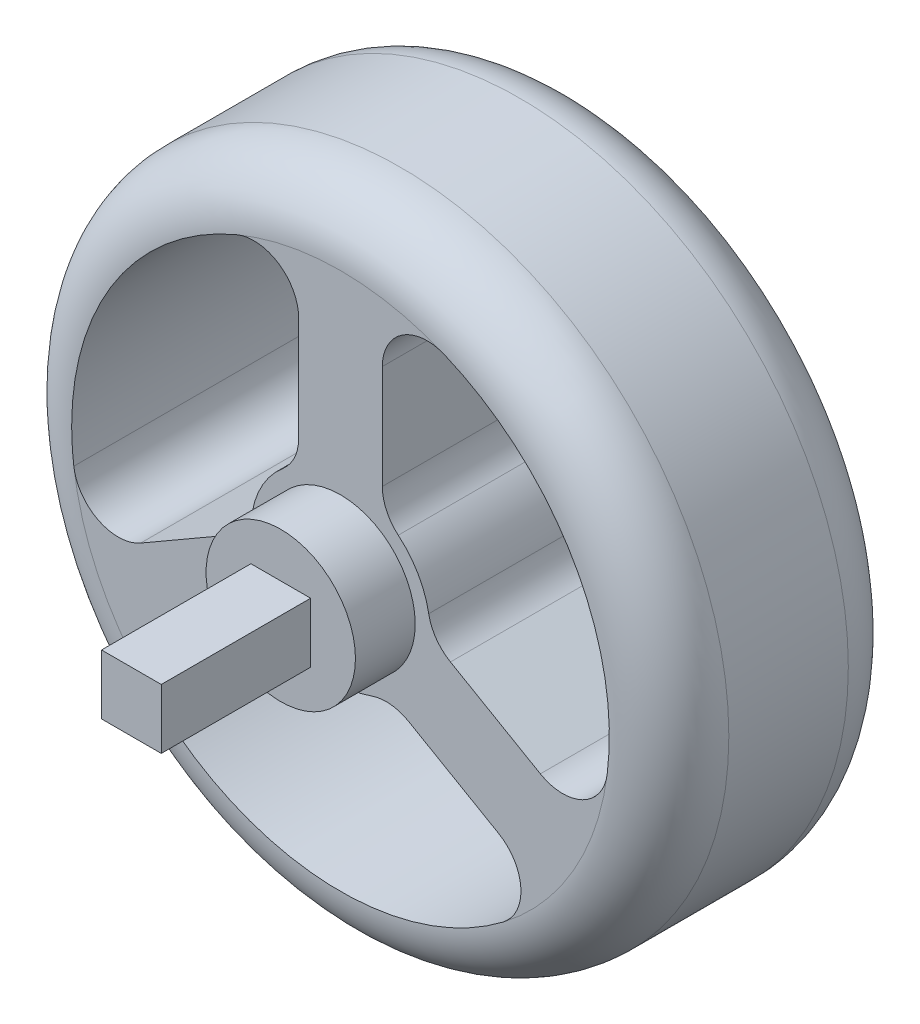
SolidWorks part; units mm, degrees
material "Rubber"
ref_plane "Front Plane" through (0, 0, 0) normal (0, 0, 1) x (1, 0, 0)
ref_plane "Top Plane" through (0, 0, 0) normal (0, 1, 0) x (1, 0, 0)
ref_plane "Right Plane" through (0, 0, 0) normal (1, 0, 0) x (0, 0, -1)
sketch "Sketch1" plane through (0, 0, 0) normal (0, 0, 1) x (1, 0, 0)
  circle A0 centre (0, 0) radius 27.94
  dimension "D1" = 55.88
extrude "Boss-Extrude1" add sketch "Sketch1" along normal blind 20.32
sketch "Sketch2" plane through (0, 0, 0) normal (0, 0, -1) x (-1, 0, 0)
  circle A0 centre (0, 0) radius 6.35
  dimension "D2" = 12.7
extrude "Boss-Extrude2" add sketch "Sketch2" along normal blind 20.32
sketch "Sketch3" plane through (0, 0, -20.32) normal (0, 0, -1) x (-1, 0, 0)
  circle A0 centre (0, 0) radius 27.94
  dimension "D2" = 55.88
extrude "Boss-Extrude3" add sketch "Sketch3" along normal blind 20.32
fillet "Fillet1" radius 5.08 1 edges at (27.94, 0, 20.32)
fillet "Fillet2" radius 5.08 1 edges at (27.94, 0, 0)
fillet "Fillet3" radius 5.08 1 edges at (-27.94, 0, -20.32)
fillet "Fillet4" radius 5.08 1 edges at (-27.94, 0, -40.64)
sketch "Sketch4" plane through (0, 0, -40.64) normal (0, 0, -1) x (-1, 0, 0)
  line L0 (0, 7.62) -> (0, 22.86) construction
  line L1 (-3.556, 8.74) -> (-3.556, 17.5683)
  line L2 (3.556, 8.74) -> (3.556, 17.5683)
  line L3 (9.347, -1.2904) -> (16.9926, -5.7046)
  line L4 (5.791, -7.4496) -> (13.4366, -11.8637)
  line L5 (-5.791, -7.4496) -> (-13.4366, -11.8637)
  line L6 (-9.347, -1.2904) -> (-16.9926, -5.7046)
  arc A0 (-13.8379, -18.1959) -> (13.8379, -18.1959) centre (0, 0) ccw
  arc A1 (7.5014, 1.3394) -> (4.9107, 5.8266) centre (0, 0) ccw
  arc A2 (-4.9107, 5.8266) -> (-7.5014, 1.3394) centre (0, 0) ccw
  arc A3 (-2.5907, -7.1661) -> (2.5907, -7.1661) centre (0, 0) ccw
  arc A4 (-3.556, 17.5683) -> (-8.8392, 21.0819) centre (-7.366, 17.5683) ccw
  arc A5 (8.8392, 21.0819) -> (3.556, 17.5683) centre (7.366, 17.5683) ccw
  arc A6 (-4.9107, 5.8266) -> (-3.556, 8.74) centre (-7.366, 8.74) ccw
  arc A7 (3.556, 8.74) -> (4.9107, 5.8266) centre (7.366, 8.74) ccw
  arc A8 (16.9926, -5.7046) -> (22.6771, -2.886) centre (18.8976, -2.405) ccw
  arc A9 (7.5014, 1.3394) -> (9.347, -1.2904) centre (11.252, 2.0092) ccw
  arc A10 (5.791, -7.4496) -> (2.5907, -7.1661) centre (3.886, -10.7491) ccw
  arc A11 (13.8379, -18.1959) -> (13.4366, -11.8637) centre (11.5316, -15.1633) ccw
  arc A12 (-13.4366, -11.8637) -> (-13.8379, -18.1959) centre (-11.5316, -15.1633) ccw
  arc A13 (-2.5907, -7.1661) -> (-5.791, -7.4496) centre (-3.886, -10.7491) ccw
  arc A14 (-9.347, -1.2904) -> (-7.5014, 1.3394) centre (-11.252, 2.0092) ccw
  arc A15 (-22.6771, -2.886) -> (-16.9926, -5.7046) centre (-18.8976, -2.405) ccw
  arc A16 (22.6771, -2.886) -> (8.8392, 21.0819) centre (0, 0) ccw
  arc A17 (-8.8392, 21.0819) -> (-22.6771, -2.886) centre (0, 0) ccw
  point P46 (0, 0)
  dimension "D2" = 45.72
  dimension "D3" = 15.24
  dimension "D6" = 7.62
  dimension "D7" = 7.62
  dimension "D8" = 7.62
  dimension "D9" = 7.62
  dimension "D4" = 3.556
  dimension "D5" = 3.556
  dimension "D10" = 3
sketch "Sketch5" plane through (0, 0, 0) normal (0, 1, 0) x (1, 0, 0)
  line L0 (0, 32.8922) -> (0, -10.16) construction
extrude "Cut-Extrude1" cut sketch "Sketch4" against normal through all
ref_plane "Plane1" through (0, 0, 0) normal (0, 0, -1) x (-1, 0, 0)
sketch "Sketch6" plane through (0, 0, 0) normal (0, 0, -1) x (-1, 0, 0)
  circle A0 centre (0, 0) radius 27.94
extrude "Cut-Extrude2" cut sketch "Sketch6" against normal through all
sketch "Sketch7" plane through (0, 0, 0) normal (0, 0, 1) x (1, 0, 0)
  circle A1 centre (0, 0) radius 6.35
  circle A2 centre (0, 0) radius 6.35
  dimension "D1" = 0
extrude "Cut-Extrude3" cut sketch "Sketch7" against normal blind 5.08
sketch "Sketch8" plane through (0, 0, -5.08) normal (0, 0, 1) x (1, 0, 0)
  line L1 (-2.54, 2.54) -> (2.54, 2.54)
  line L2 (-2.54, 2.54) -> (-2.54, -2.54)
  line L3 (-2.54, -2.54) -> (2.54, -2.54)
  line L4 (2.54, 2.54) -> (2.54, -2.54)
  line L5 (-2.54, 2.54) -> (2.54, -2.54) construction
  line L6 (-2.54, -2.54) -> (2.54, 2.54) construction
  circle A1 centre (0, 0) radius 6.35
  circle A2 centre (0, 0) radius 6.35 construction
  dimension "D2" = 5.08
  dimension "D3" = 5.08
  dimension "D1" = 0
sketch "Sketch9" plane through (0, 0, -5.08) normal (0, 0, 1) x (1, 0, 0)
  circle A1 centre (0, 0) radius 6.35
  circle A2 centre (0, 0) radius 6.35
  dimension "D1" = 0
extrude "Cut-Extrude5" cut sketch "Sketch9" against normal blind 10.16
sketch "Sketch10" plane through (0, 0, -15.24) normal (0, 0, 1) x (1, 0, 0)
  line L1 (2.54, 2.54) -> (-2.54, 2.54)
  line L2 (2.54, 2.54) -> (2.54, -2.54)
  line L3 (2.54, -2.54) -> (-2.54, -2.54)
  line L4 (-2.54, 2.54) -> (-2.54, -2.54)
  line L5 (2.54, 2.54) -> (-2.54, -2.54) construction
  line L6 (2.54, -2.54) -> (-2.54, 2.54) construction
  circle A1 centre (0, 0) radius 6.35
  circle A2 centre (0, 0) radius 6.35 construction
  dimension "D2" = 5.08
  dimension "D3" = 5.08
  dimension "D1" = 0
extrude "Boss-Extrude4" add sketch "Sketch10" along normal blind 12.7
